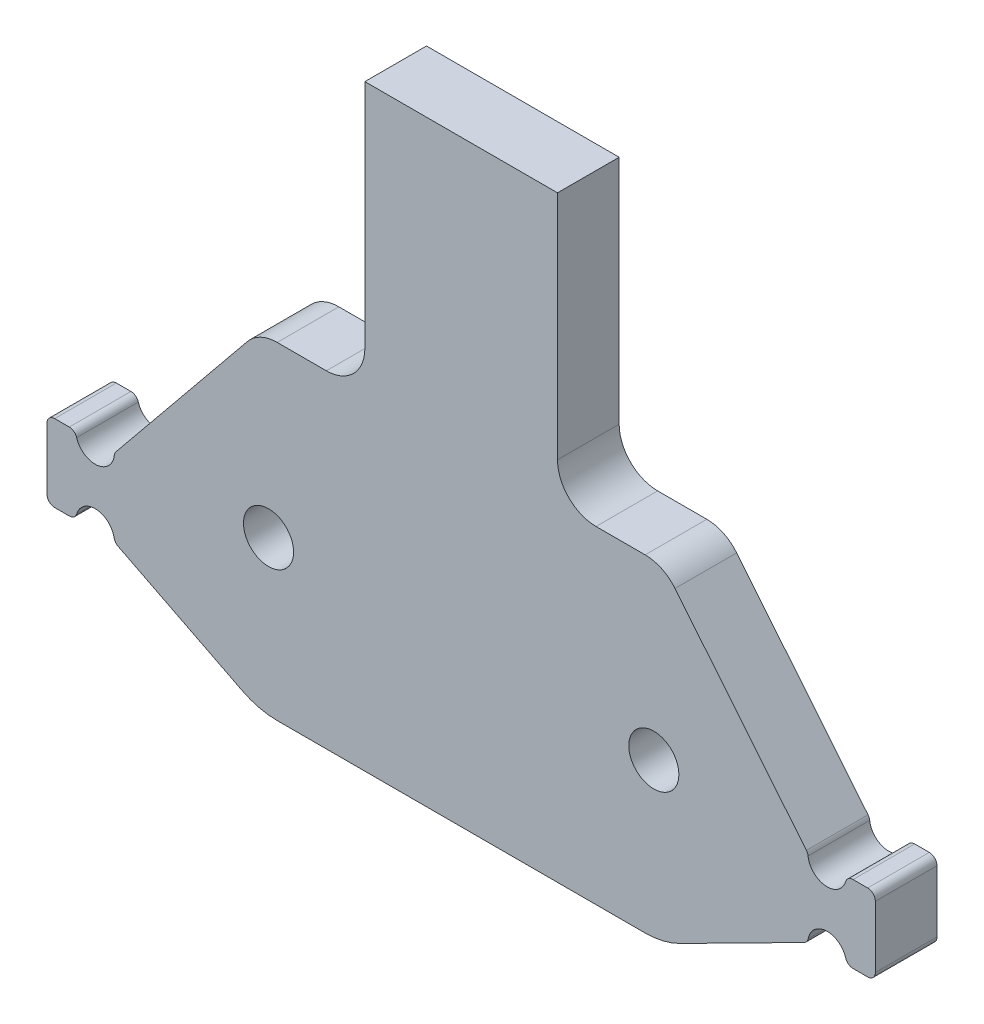
SolidWorks part; units mm, degrees
material "Q355"
ref_plane "前视基准面" through (0, 0, 0) normal (0, 0, 1) x (1, 0, 0)
ref_plane "上视基准面" through (0, 0, 0) normal (0, 1, 0) x (1, 0, 0)
ref_plane "右视基准面" through (0, 0, 0) normal (1, 0, 0) x (0, 0, -1)
sketch "草图1" plane through (0, 0, 0) normal (0, 0, 1) x (1, 0, 0)
  line L0 (0, 0) -> (0, 155) construction
  line L4 (52.5, 0) -> (90, 19)
  line L5 (-25, 155) -> (25, 155)
  line L6 (25, 155) -> (25, 85)
  line L7 (25, 85) -> (52.5, 85)
  line L8 (52.5, 85) -> (90, 39)
  line L9 (90, 39) -> (107.5, 39)
  line L10 (107.5, 39) -> (107.5, 19)
  line L11 (107.5, 19) -> (90, 19)
  line L12 (-107.5, 19) -> (-90, 19)
  line L13 (-107.5, 39) -> (-107.5, 19)
  line L14 (-90, 39) -> (-107.5, 39)
  line L15 (-52.5, 85) -> (-90, 39)
  line L16 (-25, 85) -> (-52.5, 85)
  line L17 (-25, 155) -> (-25, 85)
  line L18 (-52.5, 0) -> (-90, 19)
  line L19 (-52.5, 0) -> (52.5, 0)
  dimension "D2" = 85
  dimension "D3" = 105
  dimension "D4" = 155
  dimension "D5" = 215
  dimension "D6" = 20
  dimension "D7" = 19
  dimension "D8" = 180
  dimension "D9" = 50
  dimension "D11" = 105
extrude "凸台-拉伸3" add sketch "草图1" along normal blind 16
sketch "草图8" plane through (0, 0, 16) normal (0, 0, 1) x (1, 0, 0)
  line L0 (-90, 39) -> (-107.5, 39) construction
  line L1 (-107.5, 19) -> (-90, 19) construction
  line L2 (90, 39) -> (107.5, 39) construction
  line L3 (107.5, 19) -> (90, 19) construction
  circle A0 centre (-95, 39) radius 5
  circle A1 centre (-95, 19) radius 5
  circle A2 centre (95, 39) radius 5
  circle A3 centre (95, 19) radius 5
  dimension "D1" = 10
extrude "切除-拉伸3" cut sketch "草图8" against normal through all
sketch "草图9" plane through (0, 0, 16) normal (0, 0, 1) x (1, 0, 0)
  line L0 (0, 0) -> (0, 155) construction
  line L1 (-25, 155) -> (25, 155) construction
  line L3 (-52.5, 0) -> (52.5, 0) construction
  circle A0 centre (-50, 40) radius 6.5
  circle A1 centre (50, 40) radius 6.5
  dimension "D1" = 100
  dimension "D2" = 13
  dimension "D3" = 40
extrude "切除-拉伸4" cut sketch "草图9" against normal through all
fillet "圆角1" radius 10 2 edges at (25, 85, 8) (-25, 85, 8)
fillet "圆角2" radius 20 2 edges at (-52.5, 0, 8) (52.5, 0, 8)
fillet "圆角3" radius 2 12 edges at (-107.5, 19, 8) (-100, 19, 8) (-90, 19, 8) (-90, 39, 8) (-100, 39, 8) (-107.5, 39, 8) (90, 39, 8) (107.5, 39, 8) (100, 39, 8) (90, 19, 8) (100, 19, 8) (107.5, 19, 8)
fillet "圆角4" radius 10 2 edges at (52.5, 85, 8) (-52.5, 85, 8)
